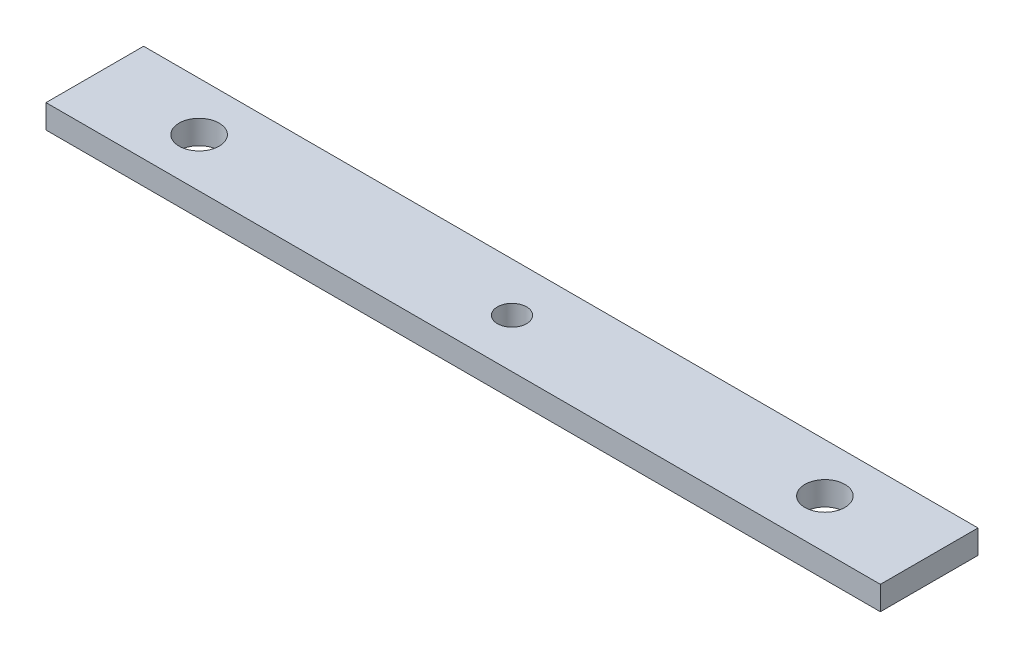
SolidWorks part; units mm, degrees
ref_plane "Front" through (0, 0, 0) normal (0, 0, 1) x (1, 0, 0)
ref_plane "Top" through (0, 0, 0) normal (0, 1, 0) x (1, 0, 0)
ref_plane "Right" through (0, 0, 0) normal (1, 0, 0) x (0, 0, -1)
sketch "Sketch1" plane through (0, 0, 0) normal (0, 1, 0) x (1, 0, 0)
  line L1 (-50, 5.85) -> (50, 5.85)
  line L2 (-50, 5.85) -> (-50, -5.85)
  line L3 (-50, -5.85) -> (50, -5.85)
  line L4 (50, 5.85) -> (50, -5.85)
  line L5 (-50, 5.85) -> (50, -5.85) construction
  line L6 (-50, -5.85) -> (50, 5.85) construction
  point P0 (0, 0)
  dimension "D1" = 11.7
  dimension "D2" = 100
extrude "Boss-Extrude1" add sketch "Sketch1" along normal blind 2.85
sketch "Sketch2" plane through (0, 2.85, 0) normal (0, 1, 0) x (1, 0, 0)
  circle A0 centre (0, 0) radius 1.75
  dimension "D1" = 3.5
extrude "Cut-Extrude3" cut sketch "Sketch2" against normal through all
extrude "Cut-Extrude4" cut sketch "Sketch3" against normal through all
sketch "Sketch3" plane through (0, -2.85, 0) normal (0, -1, 0) x (1, 0, 0)
  circle A0 centre (-37.5, 0) radius 2.4
  circle A1 centre (37.5, 0) radius 2.4
  dimension "D1" = 4.8
